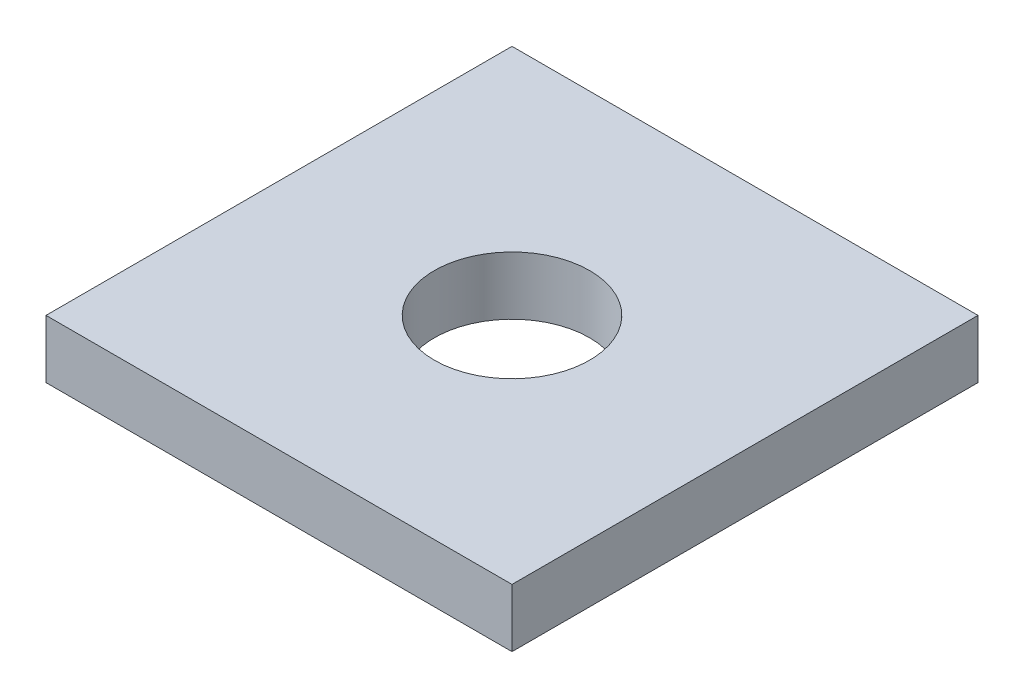
SolidWorks part; units mm, degrees
ref_plane "Front" through (0, 0, 0) normal (0, 0, 1) x (1, 0, 0)
ref_plane "Top" through (0, 0, 0) normal (0, 1, 0) x (1, 0, 0)
ref_plane "Right" through (0, 0, 0) normal (1, 0, 0) x (0, 0, -1)
sketch "Sketch1" plane through (0, 0, 0) normal (0, 1, 0) x (1, 0, 0)
  line L1 (0, 0) -> (12, 0)
  line L2 (0, 0) -> (0, 12)
  line L3 (0, 12) -> (12, 12)
  line L4 (12, 0) -> (12, 12)
  circle A0 centre (6, 6) radius 2
  dimension "D1" = 12
  dimension "D2" = 6
  dimension "D3" = 6
extrude "Boss-Extrude2" add sketch "Sketch1" along normal blind 1.5
equation "\"D2@Sketch1\"= \"D1@Sketch1\" / 2"
equation "\"D3@Sketch1\"=\"D1@Sketch1\" / 2"
